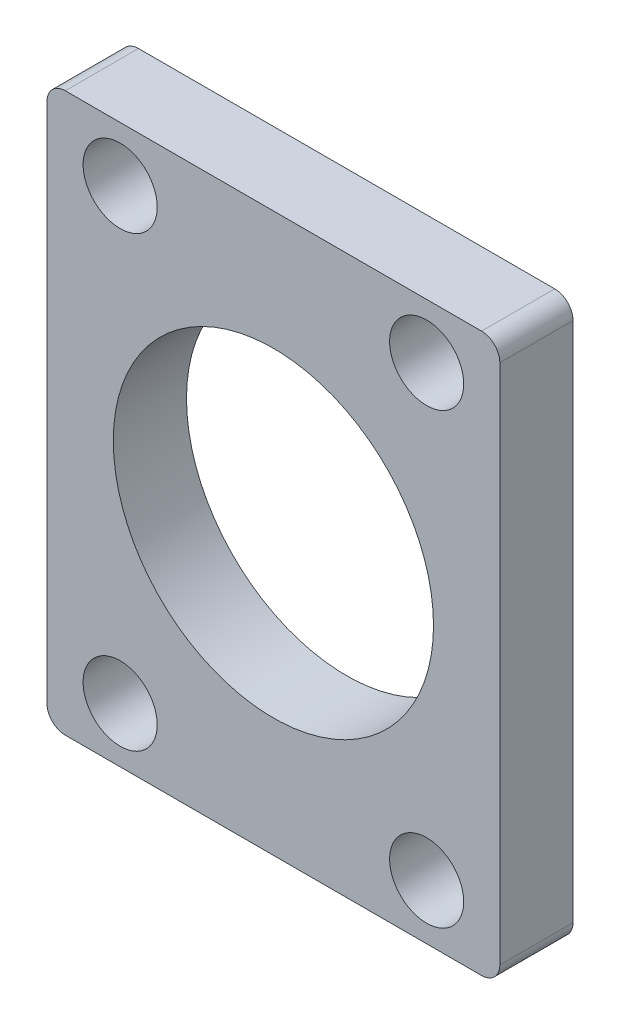
SolidWorks part; units mm, degrees
ref_plane "Front Plane" through (0, 0, 0) normal (0, 0, 1) x (1, 0, 0)
ref_plane "Top Plane" through (0, 0, 0) normal (0, 1, 0) x (1, 0, 0)
ref_plane "Right Plane" through (0, 0, 0) normal (1, 0, 0) x (0, 0, -1)
sketch "Sketch1" plane through (0, 0, 0) normal (0, 0, 1) x (1, 0, 0)
  line L0 (-351.082, -9.5) -> (-400.582, -9.5) construction
  line L1 (-400.582, -40) -> (-351.082, -40)
  line L2 (-400.582, -40) -> (-400.582, 21)
  line L3 (-400.582, 21) -> (-351.082, 21)
  line L4 (-351.082, -40) -> (-351.082, 21)
  line L5 (-400.582, -40) -> (-351.082, 21) construction
  line L6 (-400.582, 21) -> (-351.082, -40) construction
  circle A1 centre (-375.832, -9.5) radius 17.5
  dimension "D1" = 61
  dimension "D2" = 35
  dimension "D3" = 49.5
extrude "Boss-Extrude1" add sketch "Sketch1" along normal blind 8
fillet "Fillet1" radius 2 4 edges at (-400.582, 21, 4) (-351.082, 21, 4) (-351.082, -40, 4) (-400.582, -40, 4)
extrude "Cut-Extrude24" cut sketch "Sketch25" against normal blind 20
sketch "Sketch25" plane through (-362.1139, -45.1919, 10) normal (0, 0, 1) x (1, 0, 0)
  line L0 (11.0319, 35.6919) -> (-38.4681, 35.6919) construction
  line L1 (11.0319, 7.1919) -> (11.0319, 64.1919) construction
  line L2 (-38.4681, 7.1919) -> (-38.4681, 64.1919) construction
  line L3 (-13.7181, 66.1919) -> (-13.7181, 5.1919) construction
  line L4 (-36.4681, 66.1919) -> (9.0319, 66.1919) construction
  line L5 (-36.4681, 5.1919) -> (9.0319, 5.1919) construction
  circle A2 centre (-30.4681, 11.1919) radius 4.05
  circle A3 centre (-30.4681, 60.1919) radius 4.05
  circle A5 centre (3.0319, 11.1919) radius 4.05
  circle A8 centre (3.0319, 60.1919) radius 4.05
  dimension "D3" = 8.1
  dimension "D1" = 8
  dimension "D2" = 6
